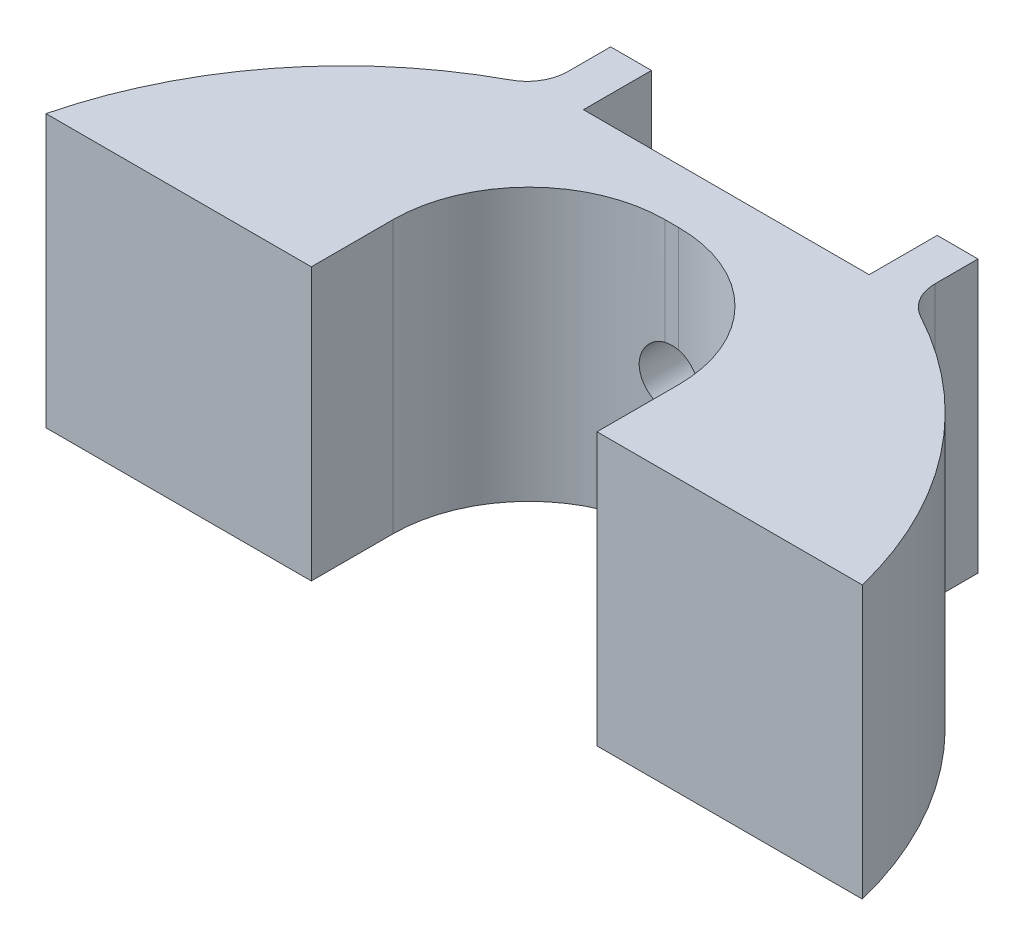
SolidWorks part; units mm, degrees
ref_plane "前视基准面" through (0, 0, 0) normal (0, 0, 1) x (1, 0, 0)
ref_plane "上视基准面" through (0, 0, 0) normal (0, 1, 0) x (1, 0, 0)
ref_plane "右视基准面" through (0, 0, 0) normal (1, 0, 0) x (0, 0, -1)
sketch "草图1" plane through (0, 0, 0) normal (0, 1, 0) x (1, 0, 0)
  line L0 (0, 0) -> (21, 0)
  line L1 (21, 0) -> (21, -4)
  line L2 (40.5, -20) -> (-19.5, -20)
  line L3 (21, -4) -> (0, -4)
  line L4 (21, 0) -> (24, 0)
  line L5 (24, 0) -> (24, 5)
  line L6 (24, 5) -> (21, 5)
  line L7 (21, 5) -> (21, 0)
  line L8 (0, 0) -> (-3, 0)
  line L9 (-3, 0) -> (-3, 5)
  line L10 (-3, 5) -> (0, 5)
  line L11 (0, 5) -> (0, 0)
  line L12 (0, -4) -> (0, 0)
  line L13 (0, -4) -> (0, -20)
  line L14 (21, -4) -> (21, -20)
  arc A0 (24, 0) -> (40.5, -20) centre (11.381, -27.2169) cw
  arc A1 (-3, 0) -> (-19.5, -20) centre (9.619, -27.2169) ccw
  dimension "D9" = 30
  dimension "D10" = 30
  dimension "D11" = 4
  dimension "D1" = 21
  dimension "D2" = 3
  dimension "D3" = 3
  dimension "D4" = 5
  dimension "D5" = 5
  dimension "D6" = 60
  dimension "D7" = 19.5
  dimension "D8" = 20
extrude "凸台-拉伸1" add sketch "草图1" along normal blind 20 contours L8 A1 L2 L13 L12 | L12 L3 L1 L0 | L11 L10 L9 L8 | L6 L7 L4 L5 | A0 L4 L1 L14 L2
fillet "圆角1" radius 10 2 edges at (0, 10, 4) (21, 10, 4)
fillet "圆角2" radius 3 2 edges at (24, 10, 0) (-3, 10, 0)
sketch "草图2" plane through (0, 0, 0) normal (0, 0, -1) x (-1, 0, 0)
  line L0 (0, 20) -> (-21, 20) construction
  line L1 (0, 20) -> (0, 0) construction
  circle A0 centre (-10.5, 10) radius 2.25
  dimension "D3" = 4.5
  dimension "D1" = 10
  dimension "D2" = 10.5
extrude "切除-拉伸1" cut sketch "草图2" against normal up to next
